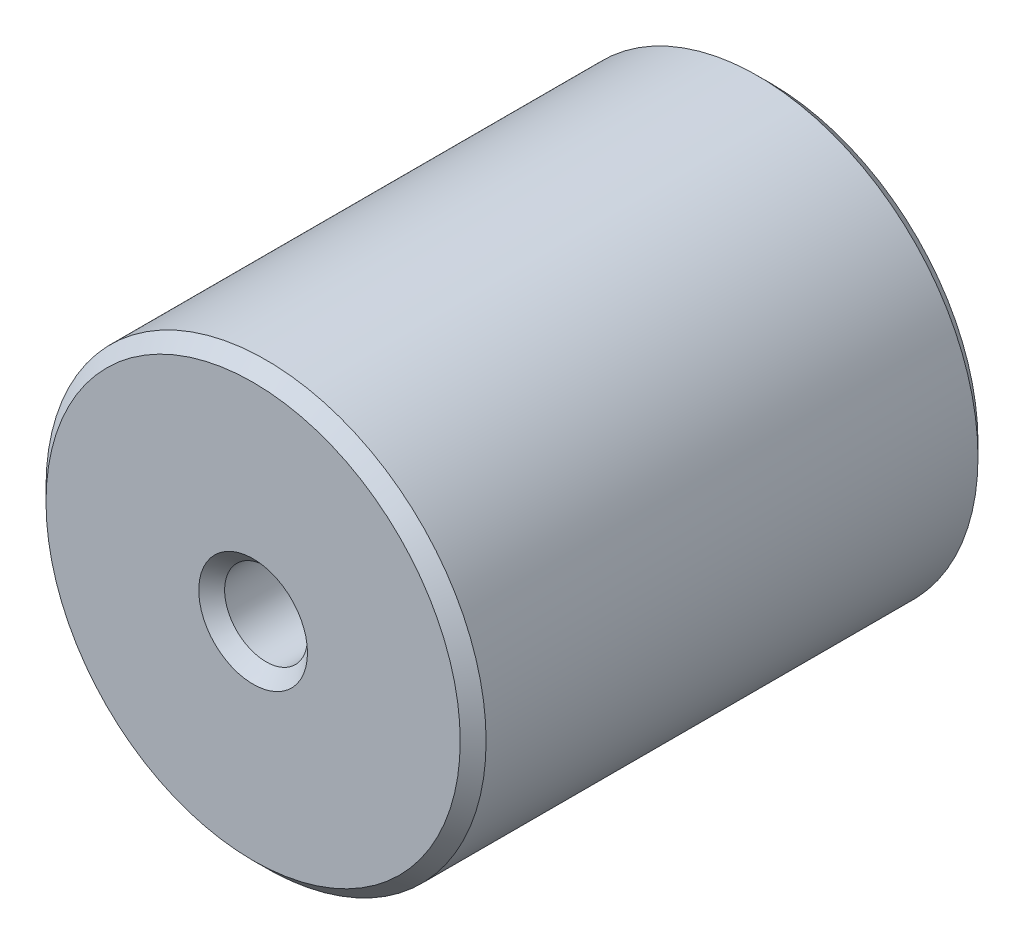
SolidWorks part; units mm, degrees
ref_plane "Plan de face" through (0, 0, 0) normal (0, 0, 1) x (1, 0, 0)
ref_plane "Plan de dessus" through (0, 0, 0) normal (0, 1, 0) x (1, 0, 0)
ref_plane "Plan de droite" through (0, 0, 0) normal (1, 0, 0) x (0, 0, -1)
sketch "Esquisse1" plane through (0, 0, 0) normal (0, 0, 1) x (1, 0, 0)
  circle A0 centre (0, 0) radius 3.2
  circle A1 centre (0, 0) radius 17
  dimension "D2" = 34
extrude "Boss.-Extru.1" add sketch "Esquisse1" along normal blind 40
chamfer "Chanfrein1" distance 1 angle 45 4 edges at (3.2, 0, 0) (3.2, 0, 40) (17, 0, 0) (17, 0, 40)
